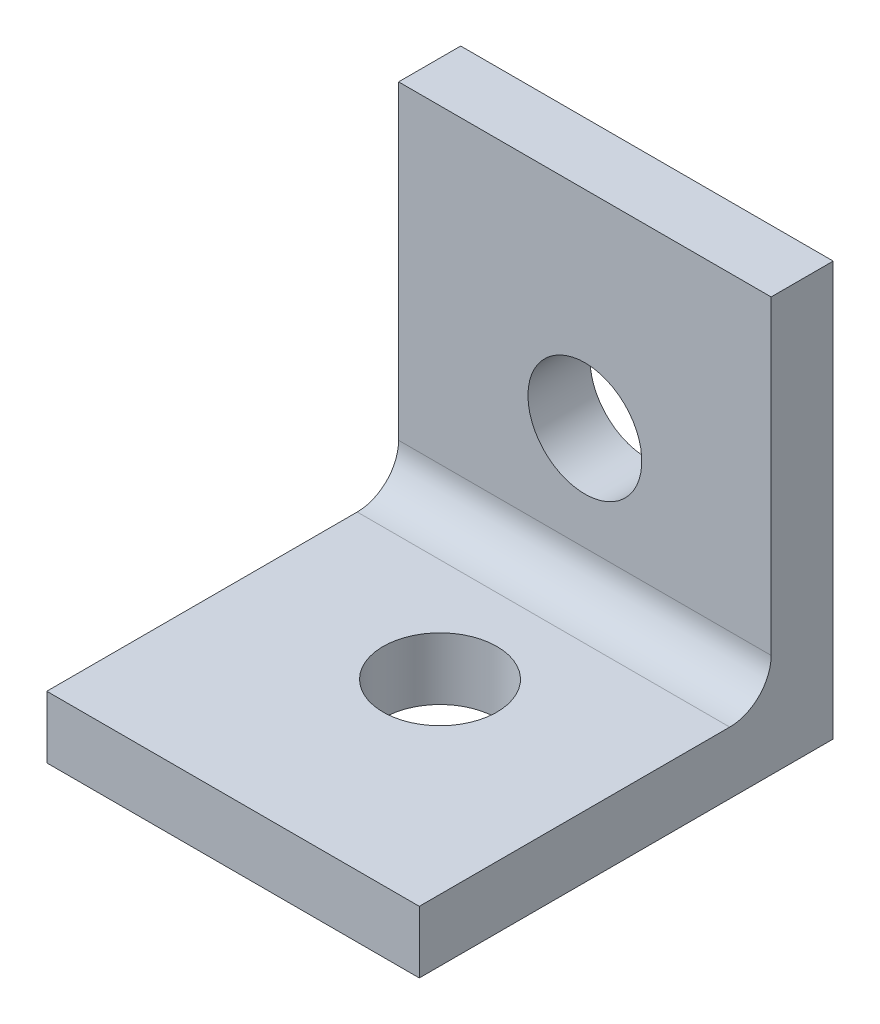
SolidWorks part; units mm, degrees
ref_plane "前视基准面" through (0, 0, 0) normal (0, 0, 1) x (1, 0, 0)
ref_plane "上视基准面" through (0, 0, 0) normal (0, 1, 0) x (1, 0, 0)
ref_plane "右视基准面" through (0, 0, 0) normal (1, 0, 0) x (0, 0, -1)
sketch "草图1" plane through (0, 0, 0) normal (0, 1, 0) x (1, 0, 0)
  line L1 (0, 0) -> (18, 0)
  line L2 (0, 0) -> (0, 20)
  line L3 (0, 20) -> (18, 20)
  line L4 (18, 0) -> (18, 20)
  dimension "D1" = 18
  dimension "D2" = 20
extrude "凸台-拉伸1" add sketch "草图1" along normal blind 3
sketch "草图2" plane through (0, 3, 0) normal (0, 1, 0) x (1, 0, 0)
  line L0 (18, 0) -> (18, 20) construction
  line L1 (0, 20) -> (18, 20)
  line L2 (0, 20) -> (0, 17)
  line L3 (0, 17) -> (18, 17)
  line L4 (18, 20) -> (18, 17)
  dimension "D1" = 3
extrude "凸台-拉伸2" add sketch "草图2" along normal blind 17
sketch "草图3" plane through (0, 0, 0) normal (0, -1, 0) x (1, 0, 0)
  line L0 (0, -20) -> (18, 0)
sketch "草图4" plane through (0, 0, 0) normal (0, -1, 0) x (-1, 0, 0)
  line L0 (0, 20) -> (-18, 0) construction
  point P0 (-9, 10)
hole_wizard "孔1" positions "草图4" profile "草图5" legacy end condition up to next
sketch "草图5" plane through (9, 0, -10) normal (1, 0, 0) x (0, 0, -1)
  line L0 (0, 0) -> (0, 3)
  line L1 (0, 3) -> (2.75, 3)
  line L2 (2.75, 3) -> (2.75, 0)
  line L3 (2.75, 0) -> (0, 0)
  line L4 (0, 110) -> (0, -10) construction
  dimension "直径" = 5.5
  dimension "深度" = 3
sketch "草图6" plane through (0, 0, -20) normal (0, 0, -1) x (-1, 0, 0)
  line L0 (-18, 0) -> (0, 20)
  line L1 (-18, 20) -> (0, 0)
sketch "草图7" plane through (0, 0, -20) normal (0, 0, -1) x (-1, 0, 0)
  line L0 (-18, 0) -> (0, 20) construction
  point P0 (-9, 10)
hole_wizard "孔2" positions "草图7" profile "草图8" legacy end condition up to next
sketch "草图8" plane through (9, 10, -20) normal (1, 0, 0) x (0, 1, 0)
  line L0 (0, 0) -> (0, 3)
  line L1 (0, 3) -> (2.75, 3)
  line L2 (2.75, 3) -> (2.75, 0)
  line L3 (2.75, 0) -> (0, 0)
  line L4 (0, 110) -> (0, -10) construction
  dimension "直径" = 5.5
  dimension "深度" = 3
fillet "圆角1" radius 2 1 edges at (9, 3, -17)
